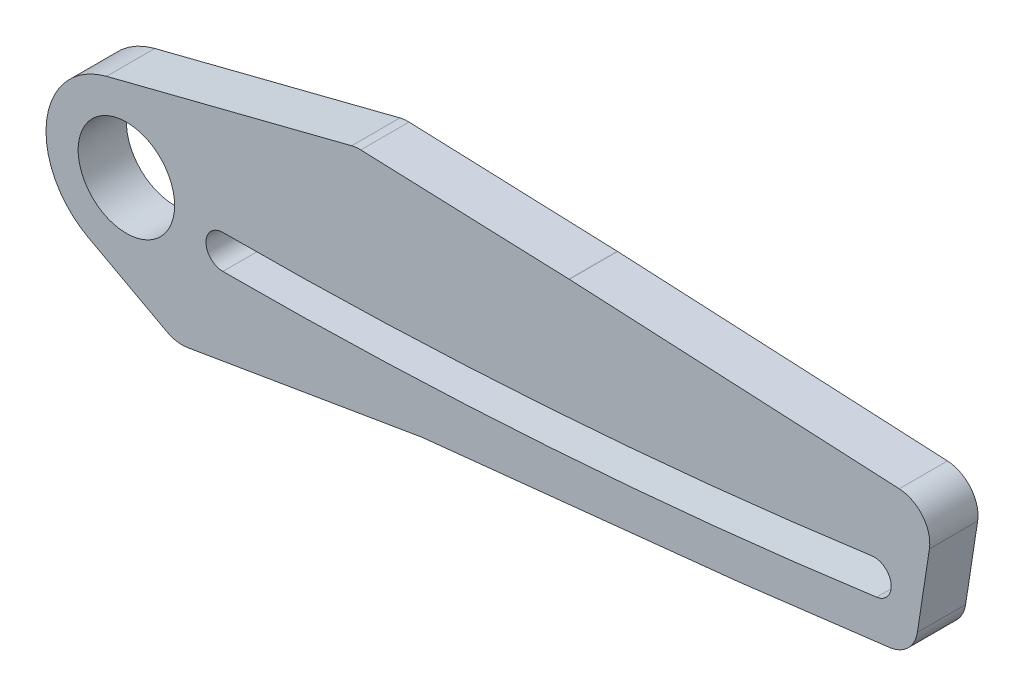
SolidWorks part; units mm, degrees
material "Thornel Mat VMA"
ref_plane "前视基准面" through (0, 0, 0) normal (0, 0, 1) x (1, 0, 0)
ref_plane "上视基准面" through (0, 0, 0) normal (0, 1, 0) x (1, 0, 0)
ref_plane "右视基准面" through (0, 0, 0) normal (1, 0, 0) x (0, 0, -1)
sketch "草图1" plane through (0, 0, 0) normal (0, 0, 1) x (1, 0, 0)
  line L0 (-1.2337, 4.8454) -> (14.2923, 8.7985)
  line L1 (50.2857, 7.1689) -> (48.9717, -1.3872)
  line L2 (48.9717, -1.3872) -> (38.1143, -2.7242)
  line L3 (38.1143, -2.7242) -> (18.3845, -4.7903)
  line L4 (-2.3728, -4.4011) -> (3.1242, -7.3648)
  line L5 (3.1242, -7.3648) -> (18.3845, -4.7903)
  line L6 (0, 0) -> (3.1242, -7.3648) construction
  line L7 (14.2923, 8.7985) -> (27.5418, 8.3025)
  line L8 (27.5418, 8.3025) -> (50.2857, 7.1689)
  circle A0 centre (0, 0) radius 3
  arc A1 (-1.2337, 4.8454) -> (-2.3728, -4.4011) centre (0, 0) ccw
  dimension "D1" = 6
  dimension "D3" = 8
extrude "凸台-拉伸1" add sketch "草图1" along normal mid plane 3
sketch "草图2" plane through (0, 0, 1.5) normal (0, 0, 1) x (1, 0, 0)
  line L0 (0, 0) -> (0, -1) construction
  line L1 (0, -1) -> (6, -1) construction
  arc A0 (6, -1) -> (46.5237, 1.777) centre (6, 296.0619) ccw construction
  arc A1 (6, -2.05) -> (46.6669, 0.7368) centre (6, 296.0619) ccw
  arc A2 (6, 0.05) -> (46.3805, 2.8172) centre (6, 296.0619) ccw
  arc A3 (6, 0.05) -> (6, -2.05) centre (6, -1) ccw
  arc A4 (46.6669, 0.7368) -> (46.3805, 2.8172) centre (46.5237, 1.777) ccw
  point P3 (26.3094, -0.3049)
  dimension "D2" = 1.05
  dimension "D1" = 1
  dimension "D3" = 6
extrude "切除-拉伸1" cut sketch "草图2" against normal blind 22
fillet "圆角1" radius 2 7 edges at (14.2923, 8.7985, 0) (27.5418, 8.3025, 0) (50.2857, 7.1689, 0) (48.9717, -1.3872, 0) (38.1143, -2.7242, 0) (18.3845, -4.7903, 0) (3.1242, -7.3648, 0)
